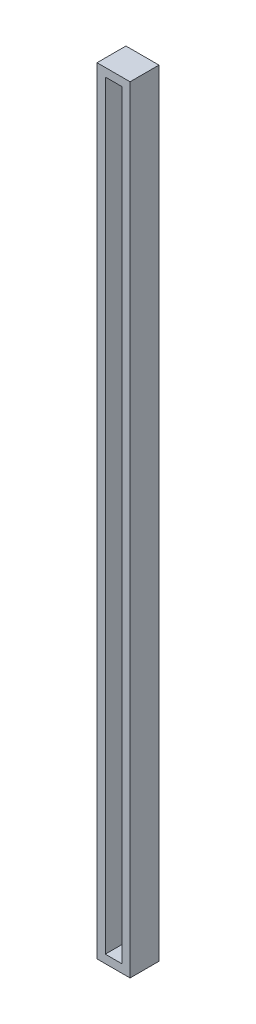
SolidWorks part; units mm, degrees
ref_plane "Front Plane" through (0, 0, 0) normal (0, 0, 1) x (1, 0, 0)
ref_plane "Top Plane" through (0, 0, 0) normal (0, 1, 0) x (1, 0, 0)
ref_plane "Right Plane" through (0, 0, 0) normal (1, 0, 0) x (0, 0, -1)
sketch "Sketch1" plane through (0, 0, 0) normal (0, 0, 1) x (1, 0, 0)
  line L1 (0, 0) -> (8, 0)
  line L2 (0, 0) -> (0, 188)
  line L3 (0, 188) -> (8, 188)
  line L4 (8, 0) -> (8, 188)
  line L6 (2, 2) -> (6, 2)
  line L7 (2, 2) -> (2, 186)
  line L8 (2, 186) -> (6, 186)
  line L9 (6, 2) -> (6, 186)
  dimension "D1" = 2
  dimension "D2" = 6
  dimension "D3" = 8
  dimension "D4" = 2
  dimension "D5" = 186
  dimension "D6" = 188
extrude "Profile" add sketch "Sketch1" along normal blind 7
equation "\"Profile_Depth\"= 7mm"
equation "\"D1@Profile\" = \"Profile_Depth\""
equation "\"Profile_Sketch_1\"= 2mm"
equation "\"D1@Sketch1\" = \"Profile_Sketch_1\""
equation "\"Profile_Sketch_2\"= 6mm"
equation "\"D2@Sketch1\" = \"Profile_Sketch_2\""
equation "\"Profile_Sketch_3\"= 8mm"
equation "\"D3@Sketch1\" = \"Profile_Sketch_3\""
equation "\"Profile_Sketch_4\"= 2mm"
equation "\"D4@Sketch1\" = \"Profile_Sketch_4\""
equation "\"Profile_Sketch_5\"= 186mm"
equation "\"D5@Sketch1\" = \"Profile_Sketch_5\""
equation "\"Profile_Sketch_6\"= 188mm"
equation "\"D6@Sketch1\" = \"Profile_Sketch_6\""
equation "\"EnvelopeWidth\"= 8mm"
equation "\"EnvelopeHeight\"= 188mm"
